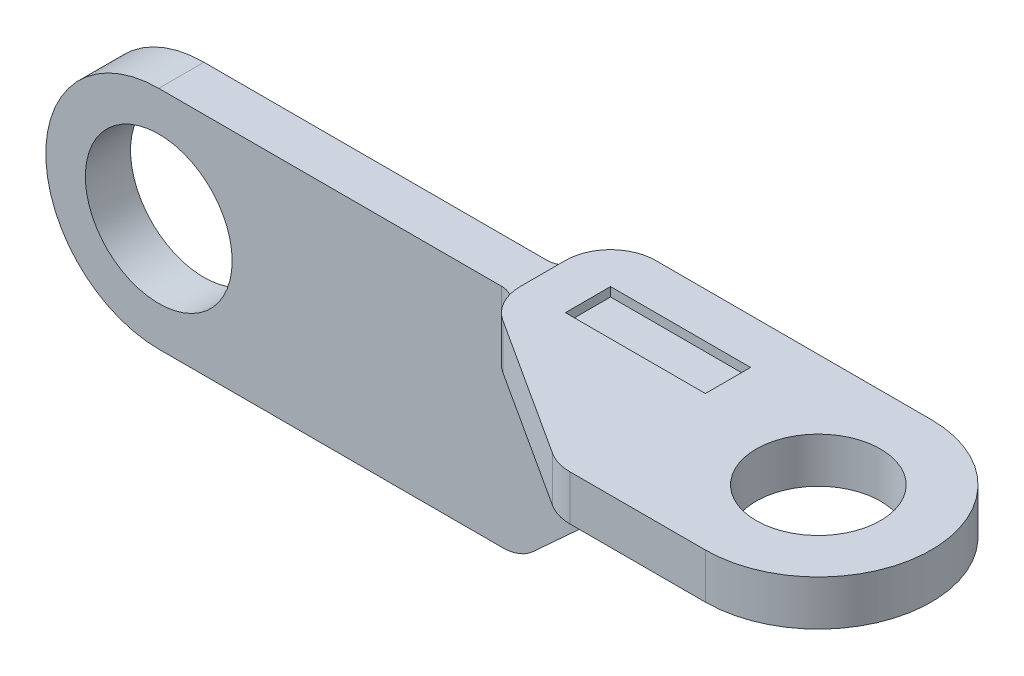
SolidWorks part; units mm, degrees
material "Copper"
ref_plane "Front Plane" through (0, 0, 0) normal (0, 0, 1) x (1, 0, 0)
ref_plane "Top Plane" through (0, 0, 0) normal (0, 1, 0) x (1, 0, 0)
ref_plane "Right Plane" through (0, 0, 0) normal (1, 0, 0) x (0, 0, -1)
sketch "Sketch12" plane through (0, 0, 0) normal (0, 1, 0) x (1, 0, 0)
  line L0 (0, 5) -> (-5, 5)
  line L1 (-5, 5) -> (-5, -5)
  line L2 (-5, -5) -> (0, -5)
  circle A0 centre (0, 0) radius 2.75
  arc A1 (0, -5) -> (0, 5) centre (0, 0) ccw
  dimension "D1" = 5.5
  dimension "D2" = 10
extrude "Boss-Extrude5" add sketch "Sketch12" along normal blind 2
sketch "Sketch20" plane through (0, 0, 0) normal (0, 0, 1) x (1, 0, 0)
  line L0 (-15.2, -8.4) -> (-15.2, 1.6)
  line L1 (-15.2, 1.6) -> (-30.2, 1.6)
  line L2 (-5, 0) -> (0, 0) construction
  line L3 (-30.2, -8.4) -> (-15.2, -8.4)
  circle A0 centre (-30.2, -3.4) radius 3.25
  arc A1 (-30.2, 1.6) -> (-30.2, -8.4) centre (-30.2, -3.4) ccw
  dimension "D1" = 10
  dimension "D2" = 6.5
  dimension "D3" = 30.2
  dimension "D4" = 3.4
  dimension "D5" = 15
extrude "Boss-Extrude6" add sketch "Sketch20" against normal blind 2 from offset 1 separate body offset against normal yes
sketch "Sketch21" plane through (0, 0, 0) normal (0, -1, 0) x (1, 0, 0)
  line L0 (-5, -5) -> (-6, -5)
  line L1 (-14.2, -3) -> (-14.2, -1)
  line L2 (-6, -5) -> (-12.2, -5)
  line L3 (-5, 5) -> (-5, -5)
  line L4 (-13.2843, 0.6806) -> (-7.0843, 4.6806)
  line L5 (-6, 5) -> (-5, 5)
  line L6 (-14.2, -2) -> (-15.2, -2) construction
  line L7 (-15.2, -3) -> (-15.2, -1) construction
  line L8 (-6, -3) -> (-12.2, -3)
  line L9 (-6, -3) -> (-6, -1)
  line L10 (-12.2, -3) -> (-12.2, -1)
  line L11 (-6, -1) -> (-12.2, -1)
  line L12 (-6, -3) -> (-12.2, -1) construction
  line L13 (-12.2, -3) -> (-6, -1) construction
  line L14 (-12.2, -2) -> (-14.2, -2) construction
  arc A0 (-12.2, -5) -> (-14.2, -3) centre (-12.2, -3) cw
  arc A1 (-14.2, -1) -> (-13.2843, 0.6806) centre (-12.2, -1) cw
  arc A2 (-7.0843, 4.6806) -> (-6, 5) centre (-6, 3) cw
  point P13 (-9.1, -2)
  point P16 (-14.2, -5)
  point P19 (-14.2, 0.0898)
  dimension "D6" = 2
  dimension "D1" = 1
  dimension "D3" = 1
  dimension "D4" = 2
  dimension "D5" = 2
extrude "Boss-Extrude7" add sketch "Sketch21" against normal blind 2
sketch "Sketch22" plane through (0, 0, -1) normal (0, 0, 1) x (1, 0, 0)
  line L0 (-6.6482, -1.474) -> (-13.6264, -7.874)
  line L1 (-14.9783, -8.4) -> (-15.2, -8.4)
  line L2 (-15.2, -8.4) -> (-15.2, 1.6)
  line L3 (-15.2, 1.6) -> (-6, 1.6)
  line L4 (-6, 1.6) -> (-6, 0)
  arc A0 (-6, 0) -> (-6.6482, -1.474) centre (-8, 0) cw
  arc A1 (-13.6264, -7.874) -> (-14.9783, -8.4) centre (-14.9783, -6.4) cw
  point P12 (-14.2, -8.4)
  dimension "D1" = 2
  dimension "D3" = 2
  dimension "D2" = 1
extrude "Boss-Extrude8" add sketch "Sketch22" against normal blind 2
fillet "Fillet1" radius 1 5 edges at (-14.2, 0.8, -3) (-14.2, 0.8, -1) (-10.1, 0, -3) (-6, 0, -2) (-10.1, 0, -1)
